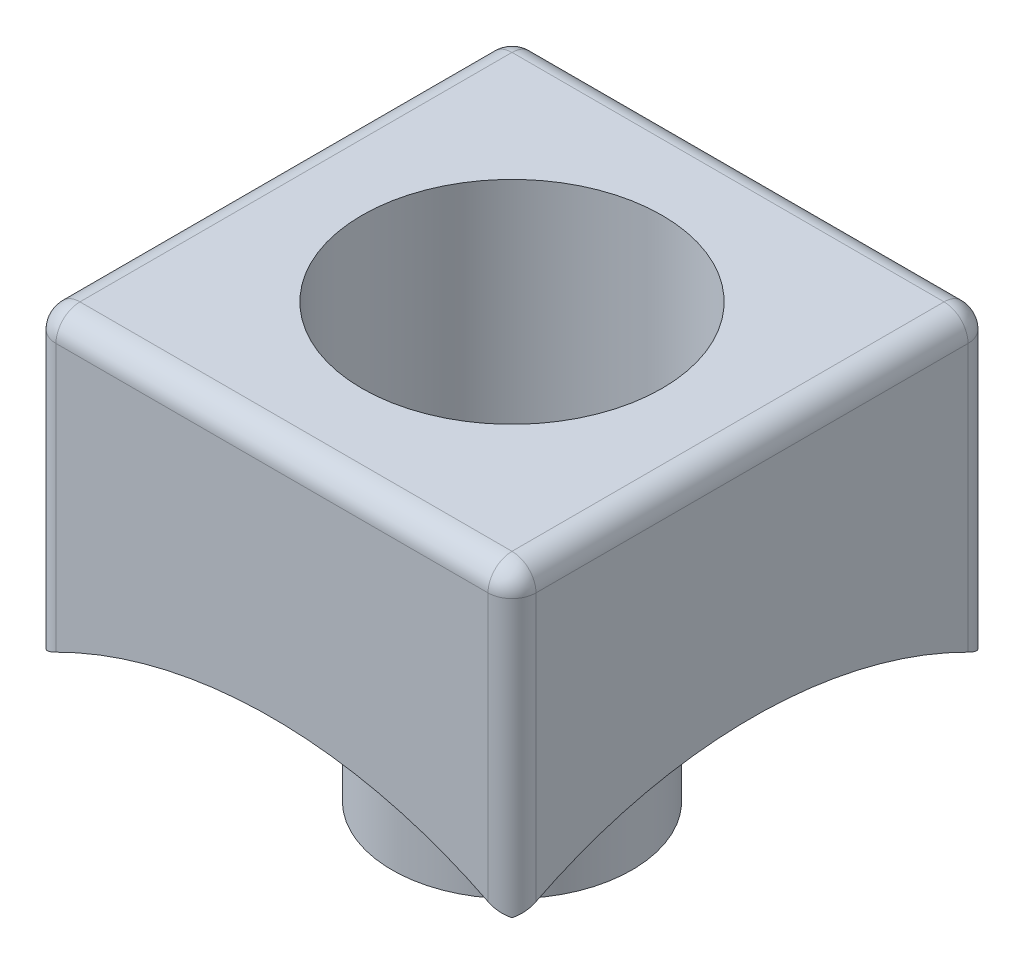
SolidWorks part; units mm, degrees
material "PS HI"
ref_plane "Ön Düzlem" through (0, 0, 0) normal (0, 0, 1) x (1, 0, 0)
ref_plane "Üst Düzlem" through (0, 0, 0) normal (0, 1, 0) x (1, 0, 0)
ref_plane "Sağ Düzlem" through (0, 0, 0) normal (1, 0, 0) x (0, 0, -1)
sketch "Çizim1" plane through (0, 0, 0) normal (0, 0, 1) x (1, 0, 0)
  line L1 (-10, -10) -> (10, -10)
  line L2 (-10, -10) -> (-10, 10)
  line L3 (-10, 10) -> (10, 10)
  line L4 (10, -10) -> (10, 10)
  line L5 (-10, -10) -> (10, 10) construction
  line L6 (-10, 10) -> (10, -10) construction
  point P0 (0, 0)
  dimension "D1" = 20
  dimension "D2" = 20
extrude "Yükseklik-Ekstrüzyon1" add sketch "Çizim1" along normal mid plane 20
shell "İç Boşaltma1" thickness 1
sketch "Çizim2" plane through (0, 9, 0) normal (0, -1, 0) x (1, 0, 0)
  circle A0 centre (0, 0) radius 7
  dimension "D1" = 14
extrude "Yükseklik-Ekstrüzyon2" add sketch "Çizim2" along normal blind 17
sketch "Çizim3" plane through (-10, 0, 0) normal (-1, 0, 0) x (0, 0, 1)
  circle A0 centre (0, -20) radius 20
extrude "Kes-Ekstrüzyon2" cut sketch "Çizim3" against normal blind 1
mirror "Aynalama1" about plane through (0, 0, 0) normal (1, 0, 0) of "Kes-Ekstrüzyon2"
sketch "Çizim4" plane through (0, 0, 10) normal (0, 0, 1) x (1, 0, 0)
  circle A0 centre (0, -20) radius 20
extrude "Kes-Ekstrüzyon3" cut sketch "Çizim4" against normal blind 1
mirror "Aynalama2" about plane through (0, 0, 0) normal (0, 0, 1) of "Kes-Ekstrüzyon3"
sketch "Çizim5" plane through (0, 10, 0) normal (0, 1, 0) x (1, 0, 0)
  circle A0 centre (0, 0) radius 6.25
  dimension "D1" = 12.5
extrude "Kes-Ekstrüzyon4" cut sketch "Çizim5" against normal blind 12
sketch "Çizim6" plane through (0, -2, 0) normal (0, 1, 0) x (1, 0, 0)
  circle A0 centre (0, 0) radius 3.25
  dimension "D1" = 6.5
extrude "Kes-Ekstrüzyon5" cut sketch "Çizim6" against normal blind 10
sketch "Çizim7" plane through (0, -8, 0) normal (0, -1, 0) x (1, 0, 0)
  circle A0 centre (0, 0) radius 8
  circle A1 centre (0, 0) radius 5
  dimension "D1" = 10
extrude "Kes-Ekstrüzyon6" cut sketch "Çizim7" against normal blind 5
fillet "Radyus2" radius 1 8 edges at (10, 3.6603, -10) (10, 3.6603, 10) (-10, 3.6603, 10) (-10, 3.6603, -10) (0, 10, -10) (10, 10, 0) (-10, 10, 0) (0, 10, 10)
